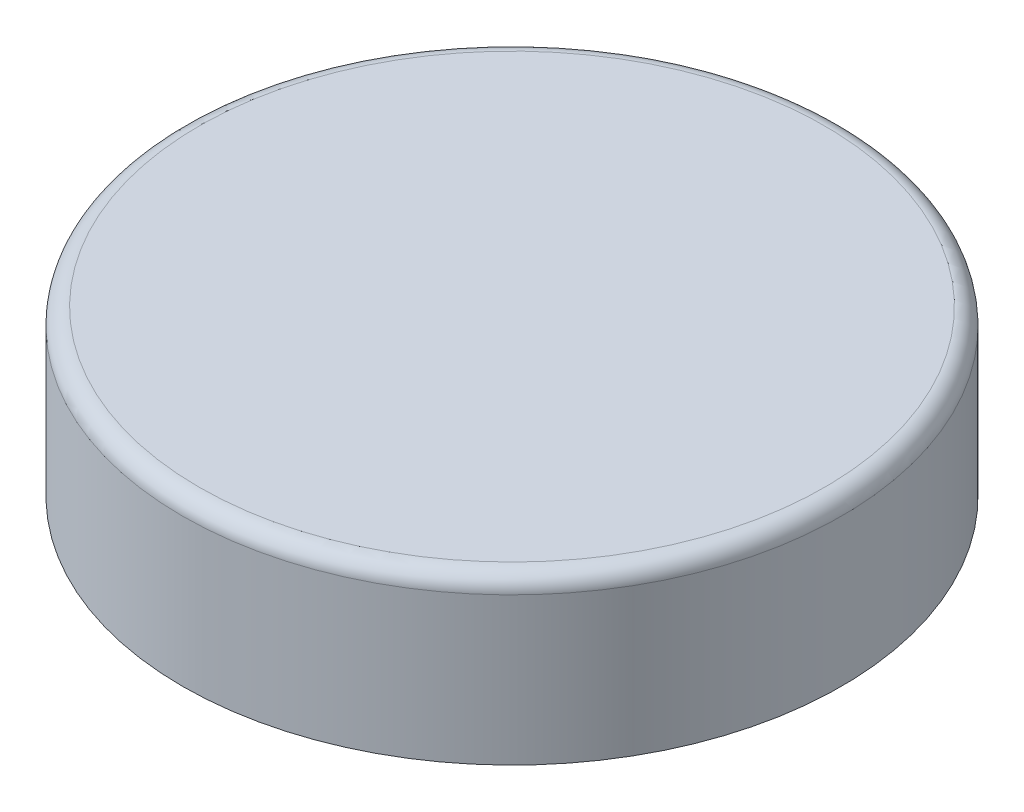
SolidWorks part; units mm, degrees
ref_plane "Front Plane" through (0, 0, 0) normal (0, 0, 1) x (1, 0, 0)
ref_plane "Top Plane" through (0, 0, 0) normal (0, 1, 0) x (1, 0, 0)
ref_plane "Right Plane" through (0, 0, 0) normal (1, 0, 0) x (0, 0, -1)
sketch "Sketch1" plane through (0, 0, 0) normal (0, 1, 0) x (1, 0, 0)
  circle A0 centre (0, 0) radius 5.925
  circle A2 centre (0, 0) radius 7.925
  circle A3 centre (0, 0) radius 4.625
  dimension "D1" = 11.85
  dimension "D2" = 1.3
  dimension "D3" = 2
extrude "Boss-Extrude1" add sketch "Sketch1" along normal blind 2.95
sketch "Sketch2" plane through (0, 2.95, 0) normal (0, 1, 0) x (1, 0, 0)
  circle A1 centre (0, 0) radius 5.925
  circle A3 centre (0, 0) radius 5.925
  dimension "D1" = 0
extrude "Boss-Extrude2" add sketch "Sketch2" against normal blind 0.4
fillet "Fillet1" radius 0.3 1 edges at (0, 2.95, 5.925)
